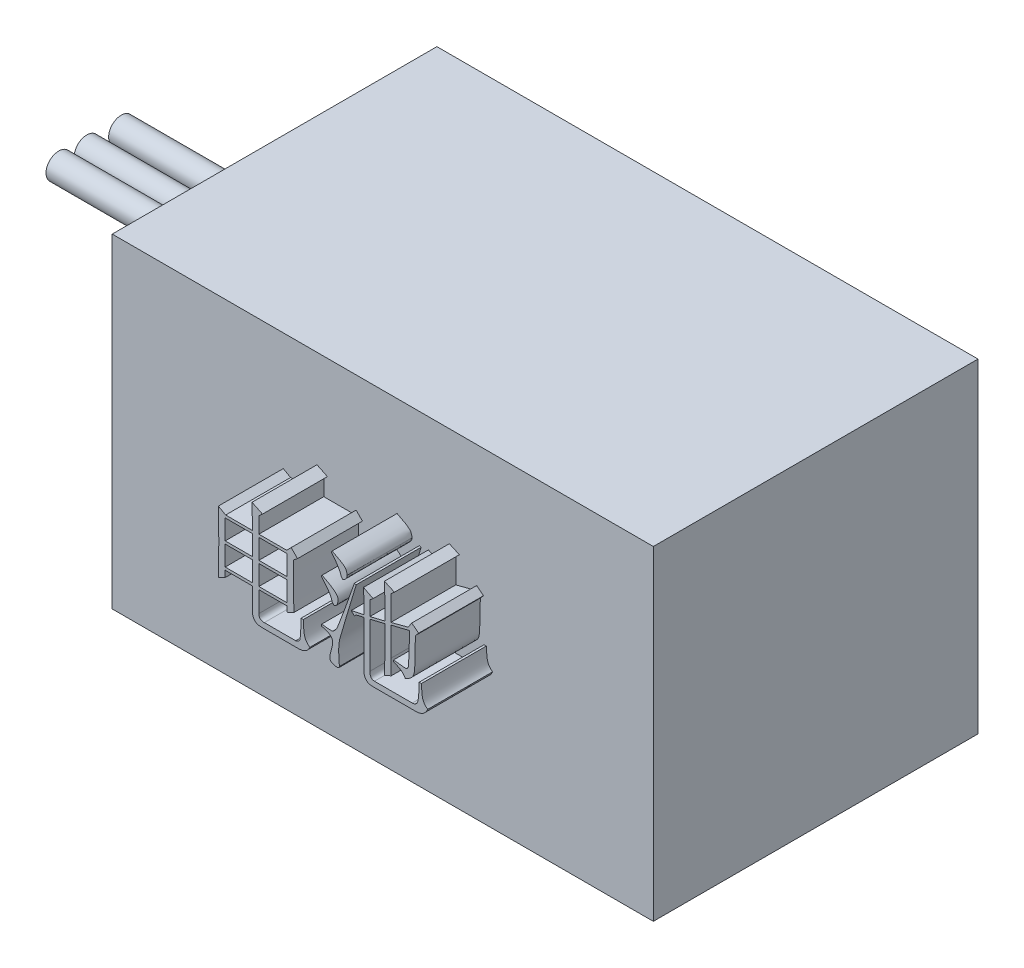
SolidWorks part; units mm, degrees
ref_plane "前视基准面" through (0, 0, 0) normal (0, 0, 1) x (1, 0, 0)
ref_plane "上视基准面" through (0, 0, 0) normal (0, 1, 0) x (1, 0, 0)
ref_plane "右视基准面" through (0, 0, 0) normal (1, 0, 0) x (0, 0, -1)
sketch "草图1" plane through (0, 0, 0) normal (0, 0, 1) x (1, 0, 0)
  line L1 (-12.5, 7.5) -> (12.5, 7.5)
  line L2 (-12.5, 7.5) -> (-12.5, -7.5)
  line L3 (-12.5, -7.5) -> (12.5, -7.5)
  line L4 (12.5, 7.5) -> (12.5, -7.5)
  line L5 (0, -7.5) -> (0, 7.5) construction
  line L6 (-12.5, 0) -> (12.5, 0) construction
  point P0 (0, 0)
  dimension "D1" = 25
  dimension "D2" = 15
extrude "凸台-拉伸1" add sketch "草图1" along normal blind 15
sketch "草图2" plane through (0, 0, 15) normal (0, 0, 1) x (1, 0, 0)
  text T0 "电池"
extrude "凸台-拉伸2" add sketch "草图2" along normal blind 3
sketch "草图3" plane through (-12.5, 0, 0) normal (-1, 0, 0) x (0, 0, 1)
  circle A0 centre (9.5853, 6.4697) radius 0.5812
  circle A1 centre (11.174, 6.4697) radius 0.5853
  circle A2 centre (12.47, 6.4697) radius 0.5901
extrude "凸台-拉伸3" add sketch "草图3" along normal blind 5
